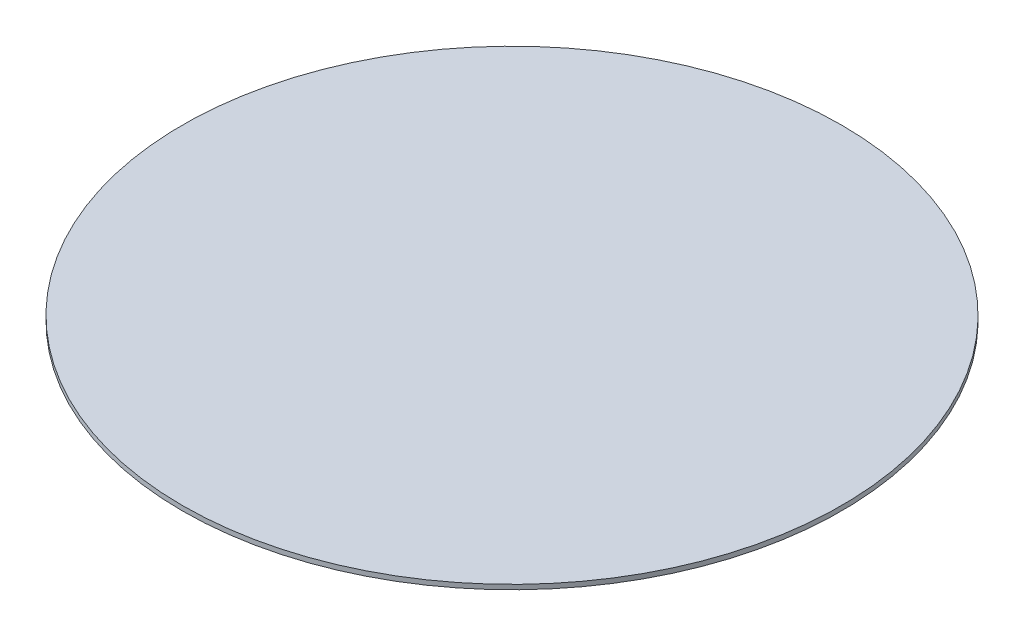
SolidWorks part; units mm, degrees
ref_plane "Front Plane" through (0, 0, 0) normal (0, 0, 1) x (1, 0, 0)
ref_plane "Top Plane" through (0, 0, 0) normal (0, 1, 0) x (1, 0, 0)
ref_plane "Right Plane" through (0, 0, 0) normal (1, 0, 0) x (0, 0, -1)
sketch "Sketch1" plane through (0, 0, 0) normal (0, 1, 0) x (1, 0, 0)
  circle A0 centre (0, 0) radius 35
extrude "Boss-Extrude1" add sketch "Sketch1" along normal blind 0.5
